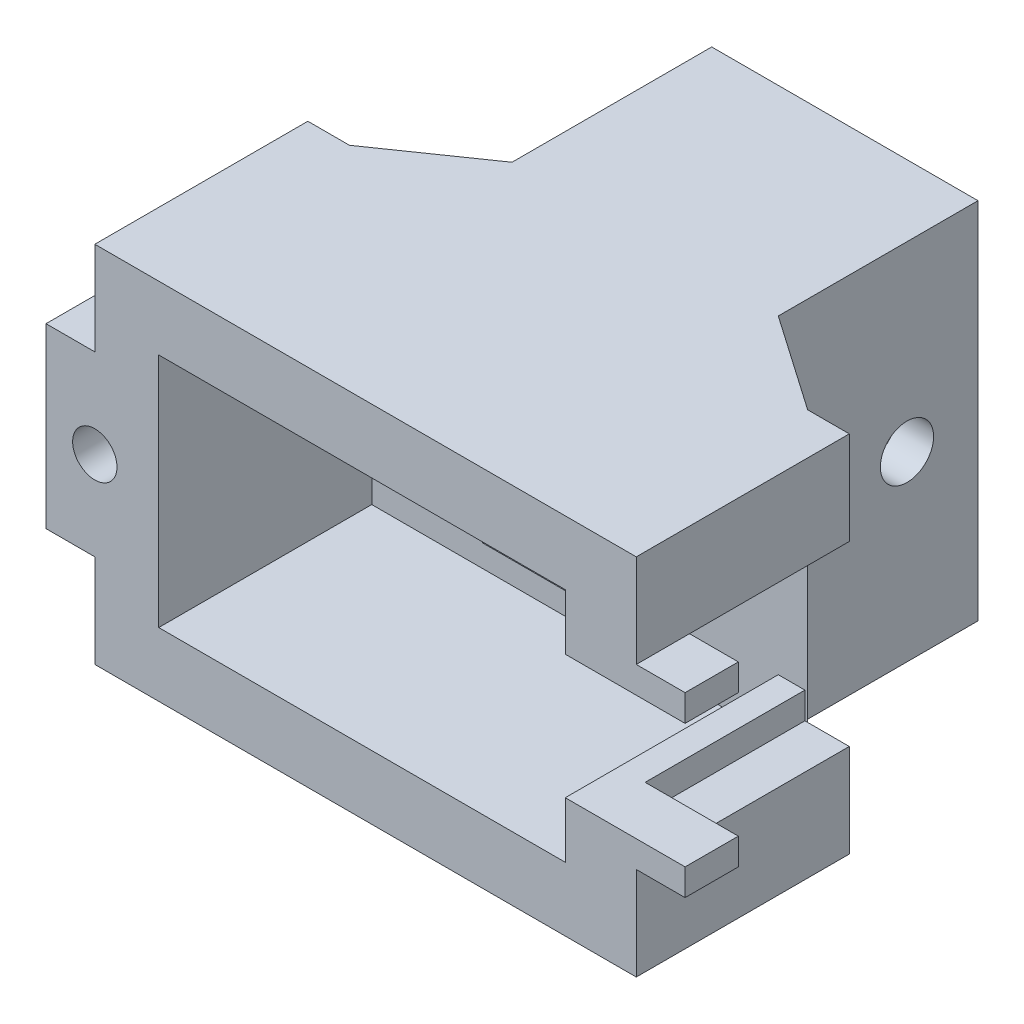
SolidWorks part; units mm, degrees
ref_plane "前视基准面" through (0, 0, 0) normal (0, 0, 1) x (1, 0, 0)
ref_plane "上视基准面" through (0, 0, 0) normal (0, 1, 0) x (1, 0, 0)
ref_plane "右视基准面" through (0, 0, 0) normal (1, 0, 0) x (0, 0, -1)
sketch "草图2" plane through (0, 0, 0) normal (0, 0, 1) x (1, 0, 0)
  line L0 (-15.25, 10.25) -> (15.25, 10.25)
  line L1 (-11.25, 6.25) -> (11.25, 6.25)
  line L2 (-11.25, 6.25) -> (-11.25, -6.25)
  line L3 (-11.25, -6.25) -> (11.25, -6.25)
  line L4 (11.25, 6.25) -> (11.25, -6.25)
  line L5 (-11.25, 6.25) -> (11.25, -6.25) construction
  line L6 (-11.25, -6.25) -> (11.25, 6.25) construction
  line L11 (-10.2, 6.25) -> (10.2, -6.25) construction
  line L12 (-10.2, -6.25) -> (10.2, 6.25) construction
  line L13 (15.25, 10.25) -> (15.25, -10.25)
  line L14 (-15.25, -10.25) -> (15.25, -10.25)
  line L15 (-15.25, 10.25) -> (-15.25, -10.25)
  point P0 (0, 0)
  point P5 (0, 0)
  dimension "D1" = 12.5
  dimension "D2" = 22.5
  dimension "D3" = 4
extrude "凸台-拉伸1" add sketch "草图2" along normal blind 12
sketch "草图3" plane through (0, 0, 12) normal (0, 0, 1) x (1, 0, 0)
  line L0 (0, 0) -> (0, 5) construction
  line L1 (-15.25, 5) -> (-18, 5)
  line L2 (-15.25, 10.25) -> (-15.25, -10.25) construction
  line L3 (-18, 5) -> (-18, -5)
  line L4 (-18, -5) -> (-15.25, -5)
  line L5 (-15.25, -5) -> (-15.25, 5)
  point P8 (-15.25, 0)
  point P10 (-16.625, -5)
  dimension "D1" = 36
  dimension "D2" = 10
extrude "凸台-拉伸2" add sketch "草图3" against normal blind 3
mirror "镜向1" about plane through (0, 0, 0) normal (1, 0, 0) of "凸台-拉伸2"
sketch "草图4" plane through (0, 0, 0) normal (0, 0, -1) x (-1, 0, 0)
  line L0 (0, 0) -> (8.8535, 0) construction
  line L1 (12.75, -5) -> (17.6907, -5)
  line L2 (12.75, -5) -> (12.75, 5)
  line L3 (12.75, 5) -> (17.6907, 5)
  line L4 (17.6907, -5) -> (17.6907, 5)
  line L5 (11.25, 6.25) -> (11.25, -6.25) construction
  dimension "D1" = 10
  dimension "D2" = 1.5
extrude "切除-拉伸1" cut sketch "草图4" against normal up to surface (9 mm away) up to face at (-16.625, 0, 9)
mirror "镜向2" about plane through (0, 0, 0) normal (1, 0, 0) of "切除-拉伸1"
sketch "草图7" plane through (0, 0, 9) normal (0, 0, -1) x (-1, 0, 0)
  line L0 (12.75, 5) -> (12.75, -5) construction
  circle A0 centre (15.25, 0) radius 1.25
  point P2 (15.4086, 0)
  dimension "D1" = 2.5
  dimension "D2" = 2.5
extrude "切除-拉伸2" cut sketch "草图7" against normal through all
sketch "草图12" plane through (0, 0, 0) normal (0, 0, -1) x (-1, 0, 0)
  line L0 (-15.25, 10.25) -> (15.25, 10.25) construction
  line L1 (-7.5, -10.25) -> (7.5, -10.25)
  line L2 (-7.5, -10.25) -> (-7.5, 10.25)
  line L3 (-7.5, 10.25) -> (7.5, 10.25)
  line L4 (7.5, -10.25) -> (7.5, 10.25)
  line L5 (-7.5, -10.25) -> (7.5, 10.25) construction
  line L6 (-7.5, 10.25) -> (7.5, -10.25) construction
  point P0 (0, 0)
  dimension "D1" = 15
extrude "凸台-拉伸5" add sketch "草图12" along normal blind 15
sketch "草图13" plane through (0, 0, -15) normal (0, 0, -1) x (-1, 0, 0)
  line L1 (5, -5) -> (-5, -5)
  line L2 (5, -5) -> (5, 5)
  line L3 (5, 5) -> (-5, 5)
  line L4 (-5, -5) -> (-5, 5)
  line L5 (5, -5) -> (-5, 5) construction
  line L6 (5, 5) -> (-5, -5) construction
  point P0 (0, 0)
  dimension "D1" = 10
  dimension "D2" = 10
extrude "切除-拉伸6" cut sketch "草图13" against normal blind 12
sketch "草图14" plane through (0, -10.25, 0) normal (0, -1, 0) x (1, 0, 0)
  line L1 (-7.5, -15) -> (-7.5, 0) construction
  line L2 (-7.5, -3.75) -> (-7.5, 0)
  line L4 (-7.5, 0) -> (-12.9051, 0)
  line L5 (-15.25, 0) -> (-7.5, 0) construction
  line L6 (-12.9051, 0) -> (-7.5, -3.75)
extrude "凸台-拉伸7" add sketch "草图14" against normal up to surface (20.5 mm away) up to face at (0, 10.25, -0.75)
mirror "镜向6" about plane through (0, 0, 0) normal (1, 0, 0) of "凸台-拉伸7"
sketch "草图15" plane through (-7.5, 0, 0) normal (-1, 0, 0) x (0, 0, 1)
  line L0 (0, 0) -> (-16.2252, 0) construction
  line L1 (-3, -5) -> (-3, 5) construction
  circle A0 centre (-11, 0) radius 1.5
  dimension "D1" = 3
  dimension "D2" = 8
extrude "切除-拉伸7" cut sketch "草图15" against normal through all
sketch "草图16" plane through (0, 0, 0) normal (0, 0, 1) x (1, 0, 0)
  line L0 (0, 0) -> (23.9668, 0) construction
  line L1 (11.25, -6.25) -> (11.25, 6.25) construction
  line L2 (11.25, -3.5) -> (21.6804, -3.5)
  line L3 (11.25, -3.5) -> (11.25, 3.5)
  line L4 (11.25, 3.5) -> (21.6804, 3.5)
  line L5 (21.6804, -3.5) -> (21.6804, 3.5)
  line L6 (11.25, -3.5) -> (21.6804, 3.5) construction
  line L7 (11.25, 3.5) -> (21.6804, -3.5) construction
  point P3 (16.4652, 0)
  dimension "D1" = 7
extrude "切除-拉伸8" cut sketch "草图16" along normal blind 23
sketch "草图17" plane through (0, 0, -15) normal (0, 0, -1) x (-1, 0, 0)
  line L14 (-5.4, -5.4) -> (5.4, -5.4)
  line L15 (5.4, -5.4) -> (5.4, 5.4)
  line L16 (5.4, 5.4) -> (-5.4, 5.4)
  line L17 (-5.4, 5.4) -> (-5.4, -5.4)
  line L18 (-5.4, -5.4) -> (5.4, -5.4)
  line L19 (5.4, -5.4) -> (5.4, 5.4)
  line L20 (5.4, 5.4) -> (-5.4, 5.4)
  line L21 (-5.4, 5.4) -> (-5.4, -5.4)
  dimension "D1" = 0.4
extrude "切除-拉伸9" cut sketch "草图17" against normal up to next
sketch "草图18" plane through (-7.5, 0, 0) normal (-1, 0, 0) x (0, 0, 1)
  line L0 (-3.75, 10.25) -> (-3.75, -10.25) construction
  line L1 (-9.2679, 3) -> (-12.7321, 3)
  line L2 (-12.7321, 3) -> (-14.4641, 0)
  line L3 (-14.4641, 0) -> (-12.7321, -3)
  line L4 (-12.7321, -3) -> (-9.2679, -3)
  line L5 (-9.2679, -3) -> (-7.5359, 0)
  line L6 (-7.5359, 0) -> (-9.2679, 3)
  circle A0 centre (-11, 0) radius 3 construction
  dimension "D1" = 6
extrude "切除-拉伸10" cut sketch "草图18" against normal up to next
sketch "草图19" plane through (0, 0, 12) normal (0, 0, 1) x (1, 0, 0)
  line L6 (11.25, 6.65) -> (11.25, -6.65)
  line L9 (-11.65, -6.65) -> (11.25, -6.65)
  line L10 (11.25, 6.65) -> (-11.65, 6.65)
  line L11 (-11.65, 6.65) -> (-11.65, -6.65)
  line L12 (-11.65, -6.65) -> (11.25, -6.65)
  line L13 (11.25, 6.65) -> (-11.65, 6.65)
  line L14 (-11.65, 6.65) -> (-11.65, -6.65)
  dimension "D1" = 0.4
extrude "切除-拉伸12" cut sketch "草图19" against normal up to surface (12 mm away) up to face at (0, 0, 0)
